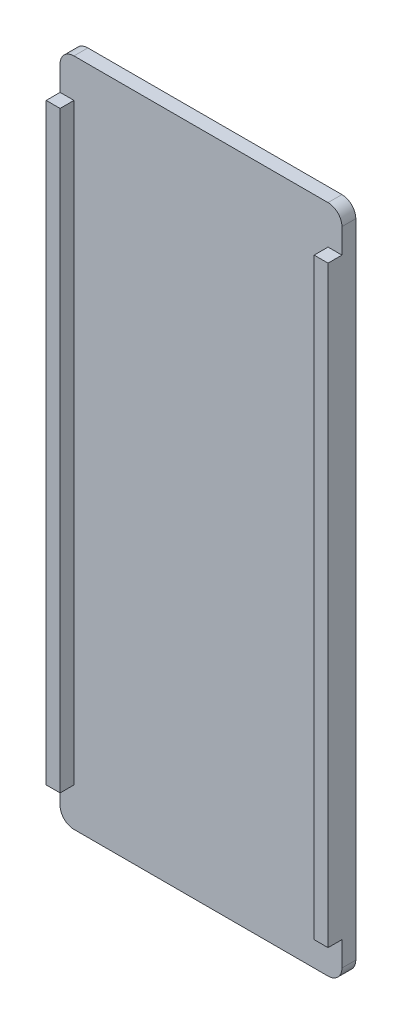
SolidWorks part; units mm, degrees
ref_plane "Ön Düzlem" through (0, 0, 0) normal (0, 0, 1) x (1, 0, 0)
ref_plane "Üst Düzlem" through (0, 0, 0) normal (0, 1, 0) x (1, 0, 0)
ref_plane "Sağ Düzlem" through (0, 0, 0) normal (1, 0, 0) x (0, 0, -1)
sketch "Çizim1" plane through (0, 0, 0) normal (0, 0, 1) x (1, 0, 0)
  line L1 (-18.3, -48.25) -> (18.3, -48.25)
  line L2 (-20.3, -46.25) -> (-20.3, 46.25)
  line L3 (-18.3, 48.25) -> (18.3, 48.25)
  line L4 (20.3, -46.25) -> (20.3, 46.25)
  line L5 (-20.3, -48.25) -> (20.3, 48.25) construction
  line L6 (-20.3, 48.25) -> (20.3, -48.25) construction
  arc A0 (-18.3, -48.25) -> (-20.3, -46.25) centre (-18.3, -46.25) cw
  arc A1 (20.3, -46.25) -> (18.3, -48.25) centre (18.3, -46.25) cw
  arc A2 (20.3, 46.25) -> (18.3, 48.25) centre (18.3, 46.25) ccw
  arc A3 (-18.3, 48.25) -> (-20.3, 46.25) centre (-18.3, 46.25) ccw
  point P0 (0, 0)
  dimension "D3" = 2
  dimension "D1" = 96.5
  dimension "D2" = 40.6
extrude "Yükseklik-Ekstrüzyon1" add sketch "Çizim1" along normal blind 2
sketch "Çizim2" plane through (0, 0, 2) normal (0, 0, 1) x (1, 0, 0)
  line L1 (-20.3, 42.7) -> (-18.3, 42.7)
  line L2 (-20.3, 42.7) -> (-20.3, -42.7)
  line L3 (-20.3, -42.7) -> (-18.3, -42.7)
  line L4 (-18.3, -48.25) -> (18.3, -48.25)
  line L5 (20.3, -46.25) -> (20.3, 46.25)
  line L6 (18.3, 48.25) -> (-18.3, 48.25)
  line L7 (-20.3, 46.25) -> (-20.3, -46.25)
  line L9 (20.3, -46.25) -> (20.3, 42.7)
  line L11 (-20.3, 42.7) -> (-20.3, -46.25)
  line L12 (-18.3, 42.7) -> (-18.3, -42.7)
  line L13 (20.3, 42.7) -> (18.3, 42.7)
  line L14 (20.3, 42.7) -> (20.3, -42.7)
  line L15 (20.3, -42.7) -> (18.3, -42.7)
  line L16 (18.3, 42.7) -> (18.3, -42.7)
  arc A4 (-20.3, -46.25) -> (-18.3, -48.25) centre (-18.3, -46.25) ccw
  arc A5 (18.3, -48.25) -> (20.3, -46.25) centre (18.3, -46.25) ccw
  arc A6 (20.3, 46.25) -> (18.3, 48.25) centre (18.3, 46.25) ccw
  arc A7 (-18.3, 48.25) -> (-20.3, 46.25) centre (-18.3, 46.25) ccw
  point P20 (18.3, -42.75)
  point P21 (18.3, 0)
  point P23 (-18.3, 0)
  line M24 (-20.3, 46.25) -> (-20.3, -46.25)
  dimension "D2" = 2
  dimension "D3" = 2
  dimension "D4" = 85.4
  dimension "D5" = 85.4
  dimension "D1" = 0
extrude "Yükseklik-Ekstrüzyon2" add sketch "Çizim2" along normal blind 2 contours L12 L1 L3 M24 | L13 L16 L15 L9
